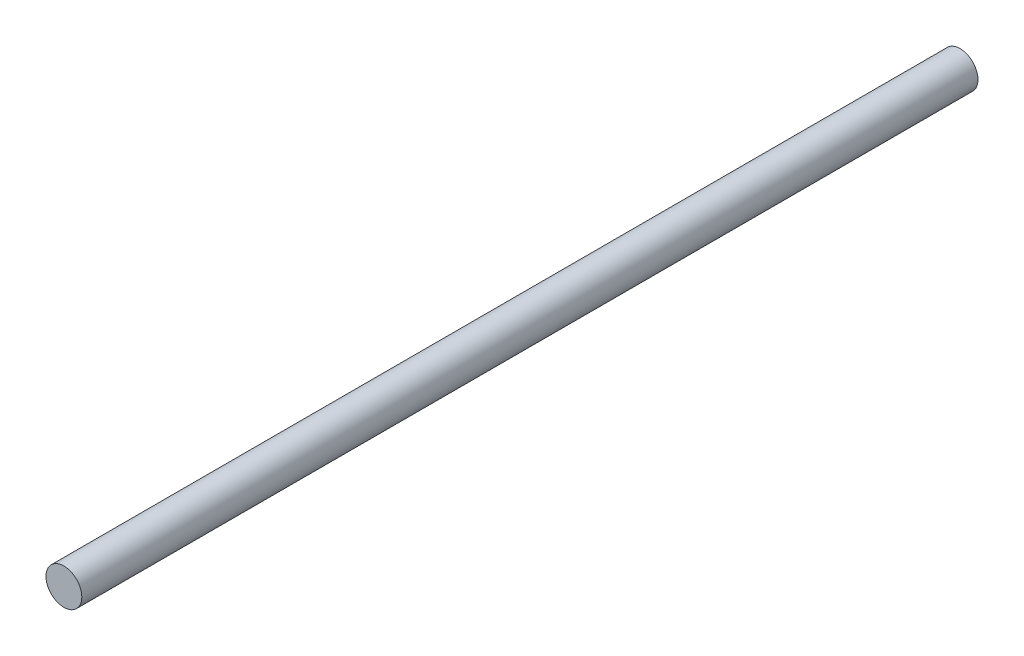
SolidWorks part; units mm, degrees
ref_plane "Front Plane" through (0, 0, 0) normal (0, 0, 1) x (1, 0, 0)
ref_plane "Top Plane" through (0, 0, 0) normal (0, 1, 0) x (1, 0, 0)
ref_plane "Right Plane" through (0, 0, 0) normal (1, 0, 0) x (0, 0, -1)
sketch "Sketch1" plane through (0, 0, 0) normal (0, 0, 1) x (1, 0, 0)
  circle A0 centre (0, 0) radius 2.5
  dimension "D1" = 5
extrude "Boss-Extrude1" add sketch "Sketch1" along normal mid plane 125
